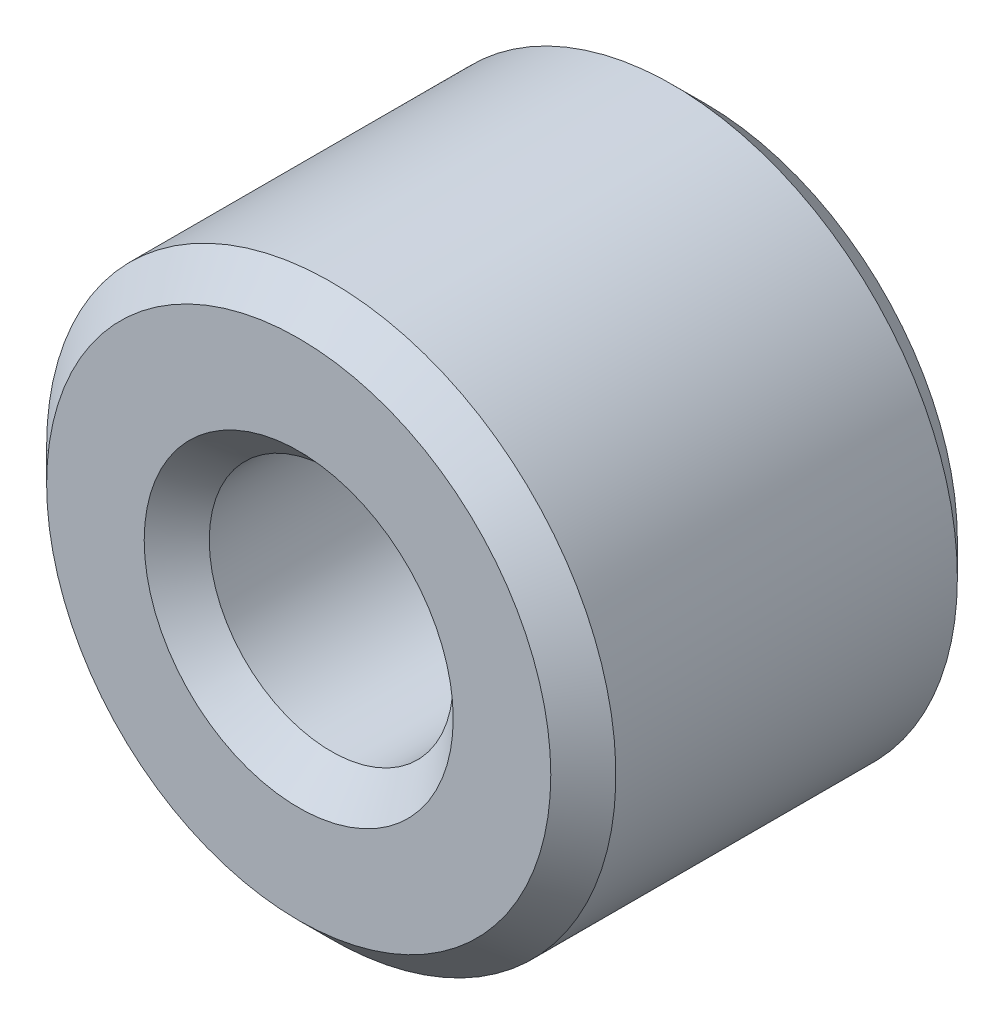
SolidWorks part; units mm, degrees
ref_plane "前视基准面" through (0, 0, 0) normal (0, 0, 1) x (1, 0, 0)
ref_plane "上视基准面" through (0, 0, 0) normal (0, 1, 0) x (1, 0, 0)
ref_plane "右视基准面" through (0, 0, 0) normal (1, 0, 0) x (0, 0, -1)
other "Configuration Table"
sketch "草图1" plane through (0, 0, 0) normal (0, 0, 1) x (1, 0, 0)
  circle A0 centre (0, 0) radius 1.5
  circle A1 centre (0, 0) radius 3.5
  dimension "D1" = 3
  dimension "D2" = 7
extrude "凸台-拉伸1" add sketch "草图1" along normal blind 5
chamfer "倒角1" distance 0.4 angle 45 4 edges at (1.5, 0, 0) (3.5, 0, 0) (1.5, 0, 5) (3.5, 0, 5)
